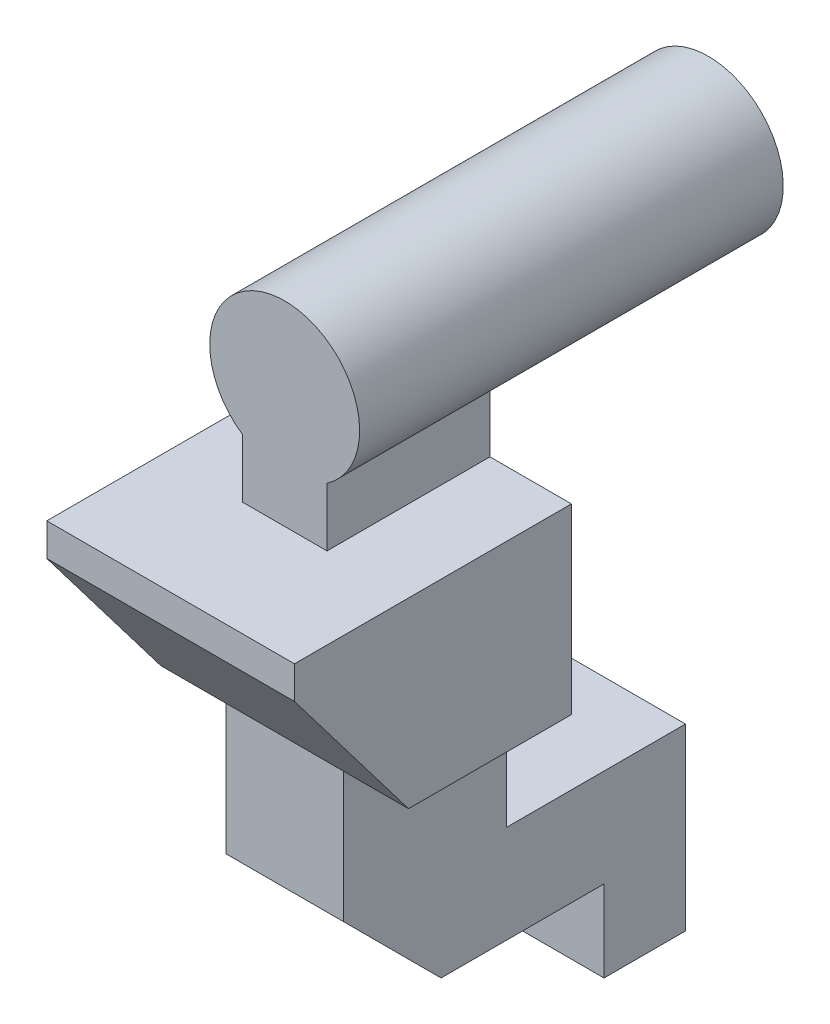
SolidWorks part; units mm, degrees
ref_plane "Płaszczyzna przednia" through (0, 0, 0) normal (0, 0, 1) x (1, 0, 0)
ref_plane "Płaszczyzna górna" through (0, 0, 0) normal (0, 1, 0) x (1, 0, 0)
ref_plane "Płaszczyzna prawa" through (0, 0, 0) normal (1, 0, 0) x (0, 0, -1)
sketch "Szkic1" plane through (0, 0, 0) normal (0, 0, 1) x (1, 0, 0)
  line L1 (-3.8, 2.8) -> (3.8, 2.8)
  line L2 (-3.8, 2.8) -> (-3.8, -2.8)
  line L3 (-3.8, -2.8) -> (3.8, -2.8)
  line L4 (3.8, 2.8) -> (3.8, -2.8)
  line L5 (-3.8, 2.8) -> (3.8, -2.8) construction
  line L6 (-3.8, -2.8) -> (3.8, 2.8) construction
  point P0 (0, 0)
  dimension "D1" = 7.6
  dimension "D2" = 5.6
extrude "Dodanie-wyciągnięcie1" add sketch "Szkic1" along normal blind 5
sketch "Szkic2" plane through (0, 0, 5) normal (0, 0, 1) x (1, 0, 0)
  line L1 (0, 0) -> (0, 10.8725) construction
  line L8 (3.8, 2.8) -> (-3.8, 2.8) construction
  line L9 (1.3, 2.8) -> (-1.3, 2.8)
  line L10 (1.3, 2.8) -> (1.3, 4.6)
  line L11 (1.3, 4.6) -> (-1.3, 4.6)
  line L12 (-1.3, 2.8) -> (-1.3, 4.6)
  line L13 (1.3, 2.8) -> (-1.3, 4.6) construction
  line L14 (1.3, 4.6) -> (-1.3, 2.8) construction
  circle A1 centre (0, 6.4974) radius 2.3
  point P12 (0, 3.7)
  point P17 (1.5, 2.8)
  point P20 (-3.8, -1.3)
  point P23 (-5.586, -1.2753)
  point P24 (-5.6026, -1.3)
  dimension "D4" = 4.6
  dimension "D5" = 2.6
  dimension "D6" = 1.8
extrude "Dodanie-wyciągnięcie2" add sketch "Szkic2" against normal up to vertex (5 mm away)
sketch "Szkic3" plane through (0, 0, 5) normal (0, 0, 1) x (1, 0, 0)
  line L0 (-1.8, -2.8) -> (-1.8, -9.8)
  line L2 (-1.8, -9.8) -> (1.8, -9.8)
  line L3 (1.8, -9.8) -> (1.8, -2.8)
  line L4 (-3.8, -2.8) -> (3.8, -2.8) construction
  line L5 (-1.8, -2.8) -> (1.8, -2.8)
  line L6 (0, 0) -> (0, -2.8) construction
  point P2 (0, 0)
  dimension "D1" = 3.6
  dimension "D2" = 7
extrude "Dodanie-wyciągnięcie3" add sketch "Szkic3" against normal up to vertex (5 mm away)
sketch "Szkic4" plane through (0, 0, 0) normal (0, 0, -1) x (-1, 0, 0)
  circle A1 centre (0, 6.4974) radius 2.3
extrude "Dodanie-wyciągnięcie4" add sketch "Szkic4" along normal blind 8
chamfer "Sfazowanie1" distance 3 angle 45 1 edges at (0, -9.8, 5)
sketch "Szkic5" plane through (3.8, 0, 0) normal (1, 0, 0) x (0, 0, -1)
  line L0 (-5, 2.8) -> (-8.5, 2.8)
  line L1 (-5, 2.8) -> (0, 2.8) construction
  line L2 (-8.5, 2.8) -> (-8.5, 1.8)
  line L3 (-8.5, 1.8) -> (-5, -2.8)
  line L4 (-5, -2.8) -> (-5, 2.8) construction
  line L5 (-5, -2.8) -> (-5, 2.8)
  line L6 (-5, -2.8) -> (0, -2.8) construction
  dimension "D1" = 3.5
  dimension "D2" = 1
extrude "Dodanie-wyciągnięcie5" add sketch "Szkic5" against normal up to vertex (7.6 mm away)
sketch "Szkic6" plane through (-1.8, 0, 0) normal (-1, 0, 0) x (0, 0, 1)
  line L0 (0, -9.8) -> (-3, -9.8)
  line L1 (0, 2.8) -> (0, -2.8) construction
  line L2 (-3, -9.8) -> (-3, -12.3)
  line L3 (-3, -12.3) -> (-5.5, -12.3)
  line L4 (-5.5, -12.3) -> (-5.5, -6.8)
  line L5 (-5.5, -6.8) -> (0, -6.8)
  line L6 (0, -9.8) -> (0, -6.8)
  point P8 (-2.354, -12.0373)
  point P9 (-5.5, -6.1756)
  point P10 (0, 0)
  dimension "D1" = 3
  dimension "D2" = 3
  dimension "D3" = 2.5
  dimension "D4" = 2.5
extrude "Dodanie-wyciągnięcie6" add sketch "Szkic6" against normal up to vertex (3.6 mm away) up to point (1.8, -9.8, 0)
